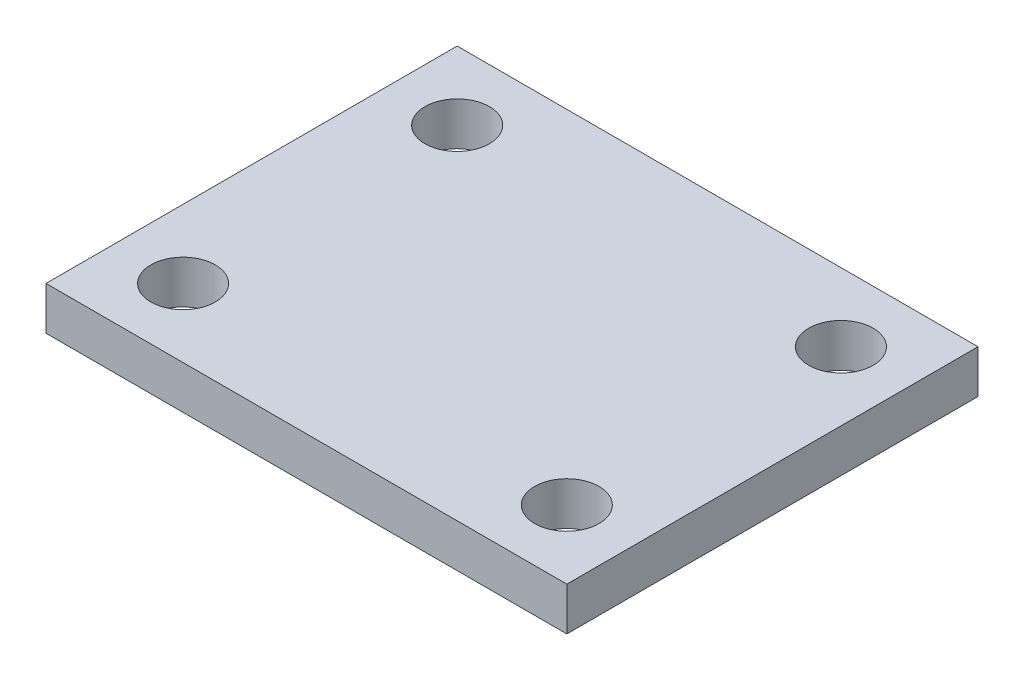
SolidWorks part; units mm, degrees
ref_plane "Front Plane" through (0, 0, 0) normal (0, 0, 1) x (1, 0, 0)
ref_plane "Top Plane" through (0, 0, 0) normal (0, 1, 0) x (1, 0, 0)
ref_plane "Right Plane" through (0, 0, 0) normal (1, 0, 0) x (0, 0, -1)
sketch "Sketch1" plane through (0, 0, 0) normal (0, 1, 0) x (1, 0, 0)
  line L0 (0, 0) -> (0, 50000) construction
  line L1 (-9.652, -7.62) -> (9.652, -7.62)
  line L2 (-9.652, -7.62) -> (-9.652, 7.62)
  line L3 (-9.652, 7.62) -> (9.652, 7.62)
  line L4 (9.652, -7.62) -> (9.652, 7.62)
  line L5 (-9.652, -7.62) -> (9.652, 7.62) construction
  line L6 (-9.652, 7.62) -> (9.652, -7.62) construction
  line L7 (0, 0) -> (50000, 0) construction
  circle A0 centre (7.112, 5.08) radius 1.1938
  circle A1 centre (7.112, -5.08) radius 1.1938
  circle A2 centre (-7.112, -5.08) radius 1.1938
  circle A3 centre (-7.112, 5.08) radius 1.1938
  point P0 (0, 0)
  dimension "D3" = 2.3876
  dimension "D4" = 2.54
  dimension "D5" = 2.54
  dimension "D1" = 19.304
  dimension "D2" = 15.24
extrude "Boss-Extrude1" add sketch "Sketch1" along normal blind 1.6
